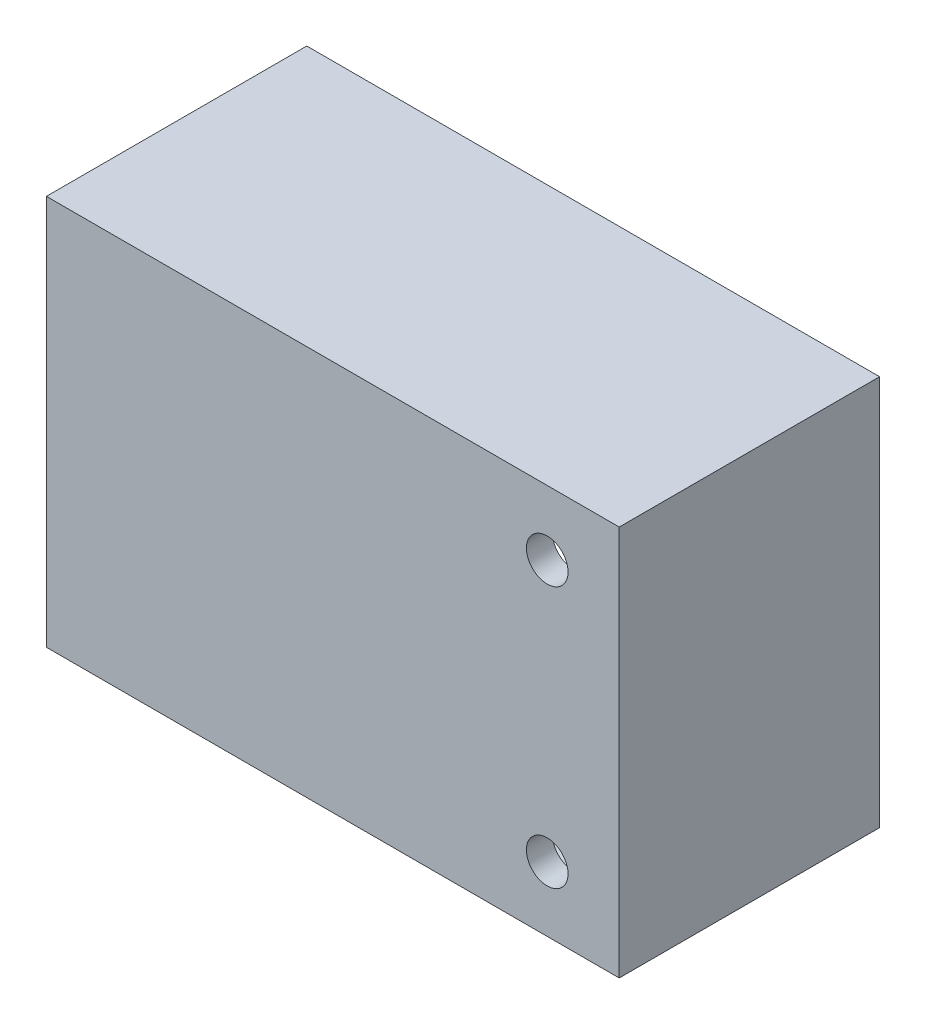
SolidWorks part; units mm, degrees
ref_plane "Plano frontal" through (0, 0, 0) normal (0, 0, 1) x (1, 0, 0)
ref_plane "Plano superior" through (0, 0, 0) normal (0, 1, 0) x (1, 0, 0)
ref_plane "Plano direito" through (0, 0, 0) normal (1, 0, 0) x (0, 0, -1)
sketch "Esboço1" plane through (0, 0, 0) normal (0, 0, 1) x (1, 0, 0)
  line L0 (2, 28) -> (42, 28)
  line L1 (0, 0) -> (44, 0)
  line L2 (0, 0) -> (0, 30)
  line L3 (0, 30) -> (44, 30)
  line L4 (44, 0) -> (44, 30)
  line L5 (42, 2) -> (42, 28)
  line L6 (2, 2) -> (42, 2)
  line L7 (2, 2) -> (2, 28)
  dimension "D1" = 2
extrude "Ressalto-extrusão1" add sketch "Esboço1" along normal blind 20
sketch "Esboço3" plane through (0, 0, 0) normal (-1, 0, 0) x (0, 0, 1)
  line L0 (20, 30) -> (0, 30) construction
  line L1 (0, 30) -> (0, 0) construction
  line L2 (20, 0) -> (0, 0) construction
  line L5 (0, 28) -> (15, 28)
  line L6 (0, 28) -> (0, 2)
  line L7 (0, 2) -> (15, 2)
  line L8 (15, 28) -> (15, 2)
  dimension "D1" = 2
  dimension "D2" = 2
  dimension "D3" = 15
extrude "Corte-extrusão1" cut sketch "Esboço3" against normal blind 20
sketch "Esboço4" plane through (0, 0, 20) normal (0, 0, 1) x (1, 0, 0)
  line L1 (0, 30) -> (44, 30)
  line L2 (0, 30) -> (0, 0)
  line L3 (0, 0) -> (44, 0)
  line L4 (44, 30) -> (44, 0)
extrude "Ressalto-extrusão2" add sketch "Esboço4" against normal blind 2
sketch "Esboço5" plane through (0, 0, 20) normal (0, 0, 1) x (1, 0, 0)
  line L0 (44, 15) -> (37.4007, 15) construction
  line L1 (44, 0) -> (44, 30) construction
  line L4 (44, 30) -> (0, 30) construction
  circle A0 centre (38.47, 25.04) radius 1.6
  circle A1 centre (38.47, 4.96) radius 1.6
  dimension "D1" = 3.2
  dimension "D2" = 5.53
  dimension "D3" = 4.96
extrude "Corte-extrusão2" cut sketch "Esboço5" against normal blind 2
